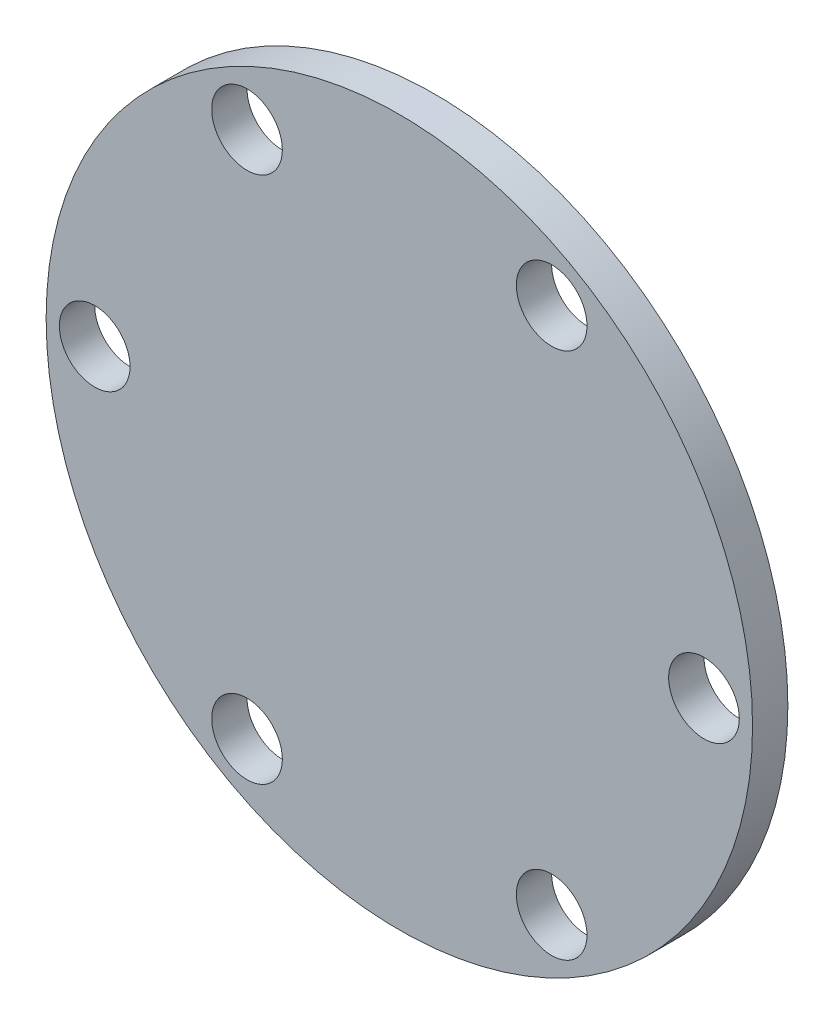
SolidWorks part; units mm, degrees
ref_plane "前视基准面" through (0, 0, 0) normal (0, 0, 1) x (1, 0, 0)
ref_plane "上视基准面" through (0, 0, 0) normal (0, 1, 0) x (1, 0, 0)
ref_plane "右视基准面" through (0, 0, 0) normal (1, 0, 0) x (0, 0, -1)
sketch "草图1" plane through (0, 0, 0) normal (0, 0, 1) x (1, 0, 0)
  circle A0 centre (0, 0) radius 20
  circle A1 centre (0, 0) radius 17.25 construction
  circle A2 centre (17.25, 0) radius 2
  circle A3 centre (8.625, -14.9389) radius 2
  circle A4 centre (-8.625, -14.9389) radius 2
  circle A5 centre (-17.25, 0) radius 2
  circle A6 centre (-8.625, 14.9389) radius 2
  circle A7 centre (8.625, 14.9389) radius 2
  point P18 (0, 0)
  dimension "D1" = 40
  dimension "D2" = 34.5
  dimension "D3" = 4
  dimension "D4" = 6
extrude "凸台-拉伸1" add sketch "草图1" along normal blind 2
